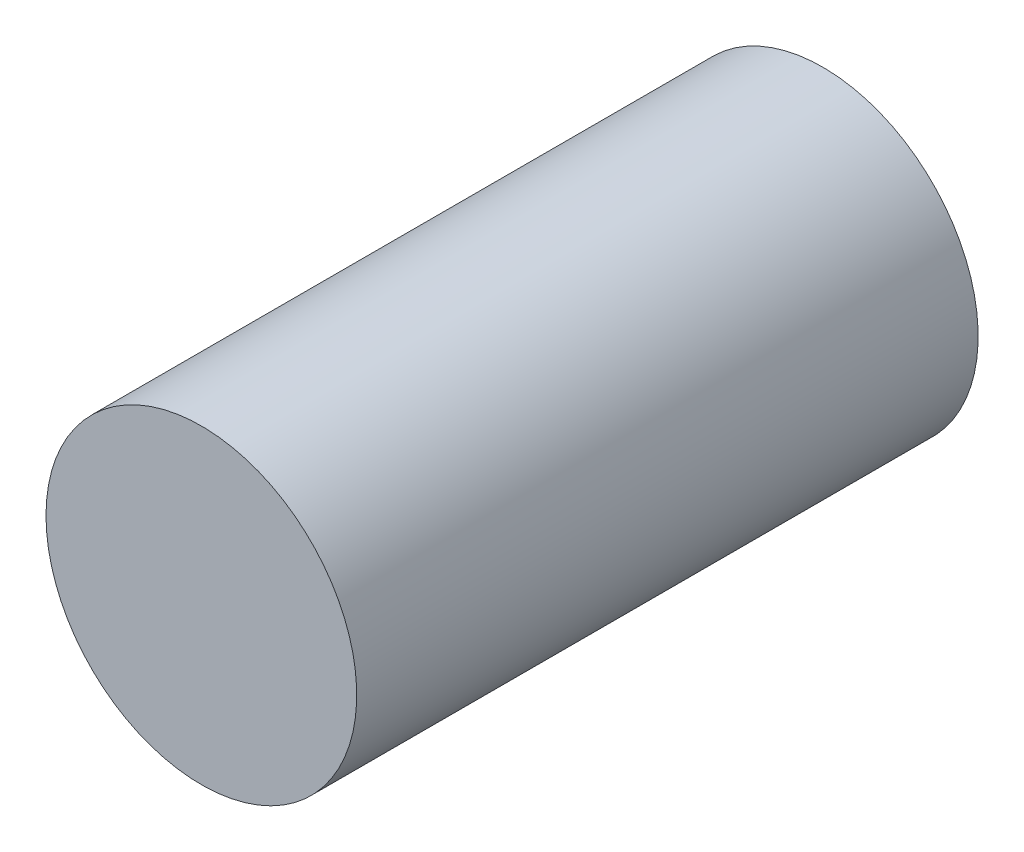
SolidWorks part; units mm, degrees
ref_plane "Face" through (0, 0, 0) normal (0, 0, 1) x (1, 0, 0)
ref_plane "Dessus" through (0, 0, 0) normal (0, 1, 0) x (1, 0, 0)
ref_plane "Droite" through (0, 0, 0) normal (1, 0, 0) x (0, 0, -1)
sketch "Esquisse1" plane through (0, 0, 0) normal (0, 0, 1) x (1, 0, 0)
  circle A0 centre (0, 0) radius 6.5
extrude "Boss.-Extru.1" add sketch "Esquisse1" along normal blind 26
